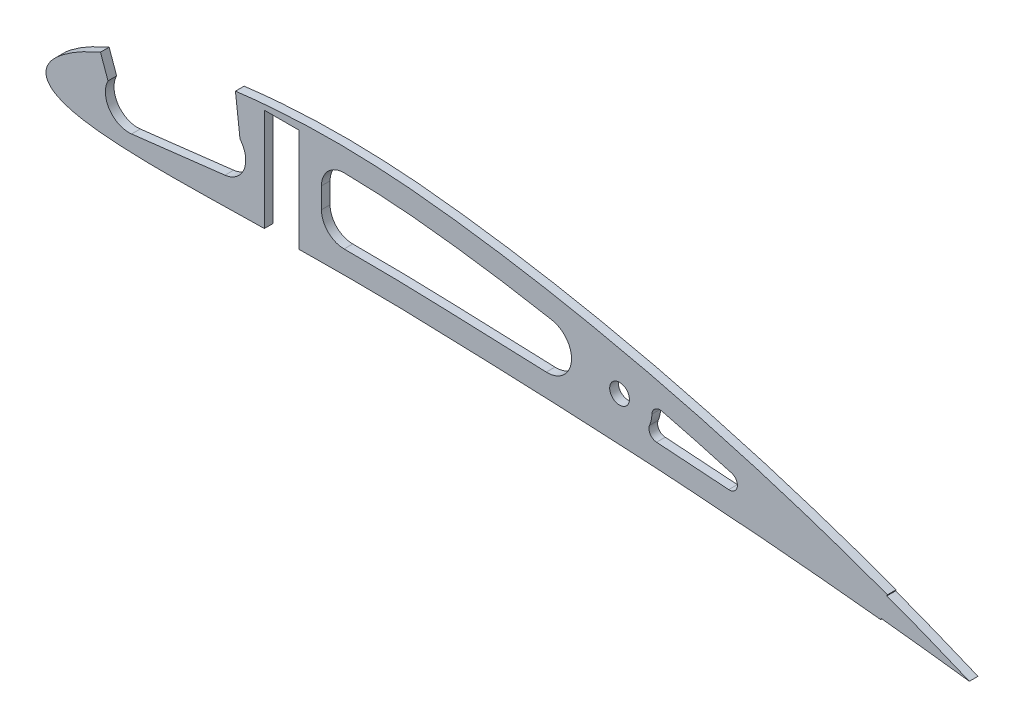
SolidWorks part; units mm, degrees
ref_plane "Front Plane" through (0, 0, 0) normal (0, 0, 1) x (1, 0, 0)
ref_plane "Top Plane" through (0, 0, 0) normal (0, 1, 0) x (1, 0, 0)
ref_plane "Right Plane" through (0, 0, 0) normal (1, 0, 0) x (0, 0, -1)
sketch "Sketch1" plane through (0, 0, 0) normal (0, 0, 1) x (1, 0, 0)
  line L0 (2483.024, 2830.9553) -> (2519.7776, 2835.2852)
  line L1 (2535.2748, 2865.1929) -> (2535.2748, 2824.843)
  line L2 (2548.8638, 2865.1929) -> (2535.2748, 2865.1929)
  line L3 (2548.8638, 2865.1929) -> (2548.8638, 2825.0881)
  line L4 (2557.7538, 2850.6377) -> (2557.7538, 2842.4734)
  line L5 (2473.7279, 2844.4024) -> (2470.7661, 2852.7101)
  line L6 (2525.6942, 2850.5244) -> (2523.8959, 2865.9934)
  line L7 (2548.8638, 2825.0881) -> (2548.8703, 2824.5678)
  line L8 (2780.3662, 2822.1316) -> (2780.5427, 2822.605)
  line L9 (2778.0193, 2813.344) -> (2777.9678, 2812.8201)
  arc A0 (2519.7776, 2835.2852) -> (2525.6942, 2850.5244) centre (2518.6951, 2844.4737) ccw
  arc A1 (2473.7279, 2844.4024) -> (2483.024, 2830.9553) centre (2481.9415, 2840.1437) ccw
  circle A2 centre (2675.1058, 2838.4418) radius 3.8862
  arc A3 (2686.9168, 2833.5701) -> (2687.8696, 2837.8792) centre (2675.1058, 2838.4418) ccw
  arc A4 (2566.7617, 2859.527) -> (2557.7538, 2850.6377) centre (2566.6438, 2850.6377) ccw
  arc A5 (2557.7538, 2842.4734) -> (2566.6631, 2833.5834) centre (2566.6438, 2842.4734) ccw
  arc A6 (2646.2636, 2831.4031) -> (2648.4261, 2850.283) centre (2646.6833, 2840.9188) ccw
  arc A7 (2691.8173, 2840.8182) -> (2687.8696, 2837.8792) centre (2691.0416, 2837.7394) ccw
  arc A8 (2686.9168, 2833.5701) -> (2689.6687, 2829.1898) centre (2689.8519, 2832.3595) ccw
  arc A9 (2718.0983, 2827.2484) -> (2719.2039, 2833.4675) centre (2718.3306, 2830.4149) ccw
  spline S0 degree 3 poles (2548.8703, 2824.5678) (2549.8808, 2824.5805) (2552.5653, 2824.6157) (2556.9478, 2824.6766) (2562.0305, 2824.6783) (2567.1738, 2824.6935) (2572.378, 2824.7092) (2577.6546, 2824.677) (2582.9782, 2824.582) (2588.3501, 2824.5361) (2593.7796, 2824.3513) (2599.3074, 2824.1972) (2604.9087, 2824.0186) (2610.5722, 2823.8665) (2616.2572, 2823.622) (2621.9699, 2823.4765) (2627.6798, 2823.2457) (2633.4021, 2823.0336) (2639.1368, 2822.8296) (2644.8687, 2822.5651) (2650.5883, 2822.3128) (2656.2963, 2822.0807) (2661.9877, 2821.7593) (2667.6718, 2821.5556) (2673.3112, 2821.2031) (2678.9152, 2820.895) (2684.4815, 2820.5755) (2690.0115, 2820.2731) (2695.4894, 2819.9276) (2700.9022, 2819.5391) (2706.2541, 2819.1681) (2711.544, 2818.7951) (2716.7484, 2818.4402) (2721.8762, 2818.0494) (2726.912, 2817.5957) (2731.8817, 2817.2416) (2736.7578, 2816.8048) (2741.5391, 2816.4156) (2746.2156, 2815.9615) (2750.7708, 2815.5361) (2755.2146, 2815.1137) (2759.5346, 2814.6951) (2763.7464, 2814.3084) (2767.8261, 2813.8427) (2771.7933, 2813.4887) (2775.1515, 2813.0925) (2777.2, 2812.8956) (2777.9678, 2812.8201) knots 19.396956 19.396956 19.396956 19.396956 19.516306 19.714059 19.914611 20.11662 20.32154 20.529276 20.739841 20.950405 21.163745 21.381461 21.603554 21.825647 22.050605 22.275616 22.500574 22.725533 22.95195 23.178326 23.403242 23.628157 23.85304 24.076496 24.299895 24.520375 24.739394 24.958414 25.174499 25.387659 25.599359 25.808139 26.013999 26.215484 26.415525 26.611171 26.803913 26.993735 27.177747 27.35884 27.534095 27.704971 27.871469 28.033634 28.189916 28.341868 28.432981 28.432981 28.432981 28.432981
  spline S1 degree 3 poles (2689.6687, 2829.1898) (2690.9236, 2829.1173) (2692.183, 2829.0421) (2699.0659, 2828.6065) (2704.6007, 2828.1943) (2712.7745, 2827.6222) (2715.4243, 2827.4446) (2718.0983, 2827.2484) knots 24.92366 24.92366 24.92366 24.92366 25.070609 25.070609 25.727122 25.727122 26.039952 26.039952 26.039952 26.039952
  spline S2 degree 3 poles (2566.6631, 2833.5834) (2567.4398, 2833.5851) (2568.2183, 2833.5868) (2573.5871, 2833.5998) (2578.3279, 2833.5445) (2585.825, 2833.4423) (2589.0364, 2833.3995) (2595.1651, 2833.2085) (2598.1673, 2833.1231) (2604.2577, 2832.9364) (2607.2482, 2832.8581) (2612.8674, 2832.6695) (2615.291, 2832.5617) (2620.1241, 2832.4104) (2622.6619, 2832.3386) (2627.6217, 2832.1496) (2630.0511, 2832.0537) (2637.0527, 2831.7969) (2641.7061, 2831.6041) (2646.2636, 2831.4031) knots 20.098452 20.098452 20.098452 20.098452 20.190363 20.190363 20.729095 20.729095 21.088164 21.088164 21.447233 21.447233 21.806302 21.806302 22.096768 22.096768 22.387234 22.387234 22.677701 22.677701 23.217184 23.217184 23.217184 23.217184
  spline S3 degree 3 poles (2780.5427, 2822.605) (2778.253, 2823.459) (2775.9733, 2824.3283) (2770.711, 2826.2113) (2767.7251, 2827.2634) (2758.7488, 2830.4525) (2752.6839, 2832.44) (2740.5388, 2836.3574) (2734.4556, 2838.2784) (2722.2133, 2841.8798) (2716.0661, 2843.5978) (2703.7593, 2846.9955) (2697.5661, 2848.5351) (2685.1978, 2851.6568) (2678.9801, 2853.0408) (2659.2455, 2857.381) (2645.7434, 2859.9547) (2623.3857, 2863.5044) (2614.7201, 2864.7281) (2599.842, 2866.4397) (2593.7119, 2867.1054) (2581.3916, 2867.9581) (2575.2189, 2868.251) (2562.8836, 2868.5069) (2556.7118, 2868.4426) (2544.3747, 2867.9374) (2538.2135, 2867.5376) (2529.344, 2866.657) (2526.6172, 2866.346) (2523.8959, 2865.9934) knots 1.615896 1.615896 1.615896 1.615896 1.904436 1.904436 2.277217 2.277217 3.031526 3.031526 3.785836 3.785836 4.540146 4.540146 5.294456 5.294456 6.048766 6.048766 7.680004 7.680004 8.718619 8.718619 9.449269 9.449269 10.17992 10.17992 10.910571 10.910571 11.641222 11.641222 11.966163 11.966163 11.966163 11.966163
  spline S4 degree 3 poles (2719.2039, 2833.4675) (2714.2381, 2834.888) (2709.2315, 2836.291) (2700.185, 2838.7081) (2696.0201, 2839.7593) (2691.8173, 2840.8182) knots 4.06038 4.06038 4.06038 4.06038 4.675696 4.675696 5.188469 5.188469 5.188469 5.188469
  spline S5 degree 3 poles (2648.4261, 2850.283) (2641.5924, 2851.5549) (2634.7338, 2852.723) (2619.3252, 2855.1083) (2610.8711, 2856.2413) (2595.7157, 2857.9455) (2589.3146, 2858.5444) (2577.4277, 2859.245) (2572.0848, 2859.4563) (2566.7617, 2859.527) knots 6.961493 6.961493 6.961493 6.961493 7.794516 7.794516 8.825426 8.825426 9.617156 9.617156 10.265753 10.265753 10.265753 10.265753
  spline S6 degree 3 poles (2470.7661, 2852.7101) (2470.6464, 2852.6581) (2470.5267, 2852.6058) (2466.9137, 2851.0197) (2463.4641, 2849.3443) (2457.8844, 2845.9155) (2455.6089, 2844.3221) (2451.9641, 2840.9753) (2450.4657, 2839.2474) (2449.2892, 2836.0407) (2449.1568, 2834.7398) (2449.952, 2832.364) (2450.8099, 2831.3148) (2452.68, 2829.8324) (2453.701, 2829.2749) (2455.7378, 2828.3358) (2456.8244, 2827.965) (2460.2041, 2826.9074) (2462.5683, 2826.4474) (2467.3207, 2825.6718) (2469.7198, 2825.406) (2476.9483, 2824.7645) (2481.785, 2824.5112) (2491.4695, 2824.2812) (2496.312, 2824.2699) (2511.0794, 2824.3539) (2520.9791, 2824.5843) (2532.35, 2824.787) (2533.8124, 2824.8148) (2535.2748, 2824.843) knots 14.135709 14.135709 14.135709 14.135709 14.151211 14.151211 14.604184 14.604184 14.932416 14.932416 15.199765 15.199765 15.362932 15.362932 15.5261 15.5261 15.66286 15.66286 15.79962 15.79962 16.086125 16.086125 16.37263 16.37263 16.945639 16.945639 17.518648 17.518648 18.689255 18.689255 18.862005 18.862005 18.862005 18.862005
  spline S7 degree 3 poles (2812.8112, 2809.2486) (2811.7427, 2809.6956) (2810.661, 2810.1411) (2805.162, 2812.4219) (2800.7468, 2814.2097) (2791.811, 2817.8309) (2787.3909, 2819.5264) (2782.0553, 2821.5049) (2781.2108, 2821.8184) (2780.3662, 2822.1316) knots 0.240373 0.240373 0.240373 0.240373 0.376825 0.376825 0.943228 0.943228 1.509632 1.509632 1.616177 1.616177 1.616177 1.616177
  spline S8 degree 3 poles (2778.0193, 2813.344) (2779.1748, 2813.217) (2780.3303, 2813.0875) (2787.9969, 2812.2098) (2794.5403, 2811.5009) (2804.9356, 2810.2216) (2808.8293, 2809.7017) (2812.8112, 2809.2486) knots 28.432747 28.432747 28.432747 28.432747 28.56999 28.56999 29.343341 29.343341 29.813814 29.813814 29.813814 29.813814
extrude "Boss-Extrude1" add sketch "Sketch1" along normal blind 3.4036
